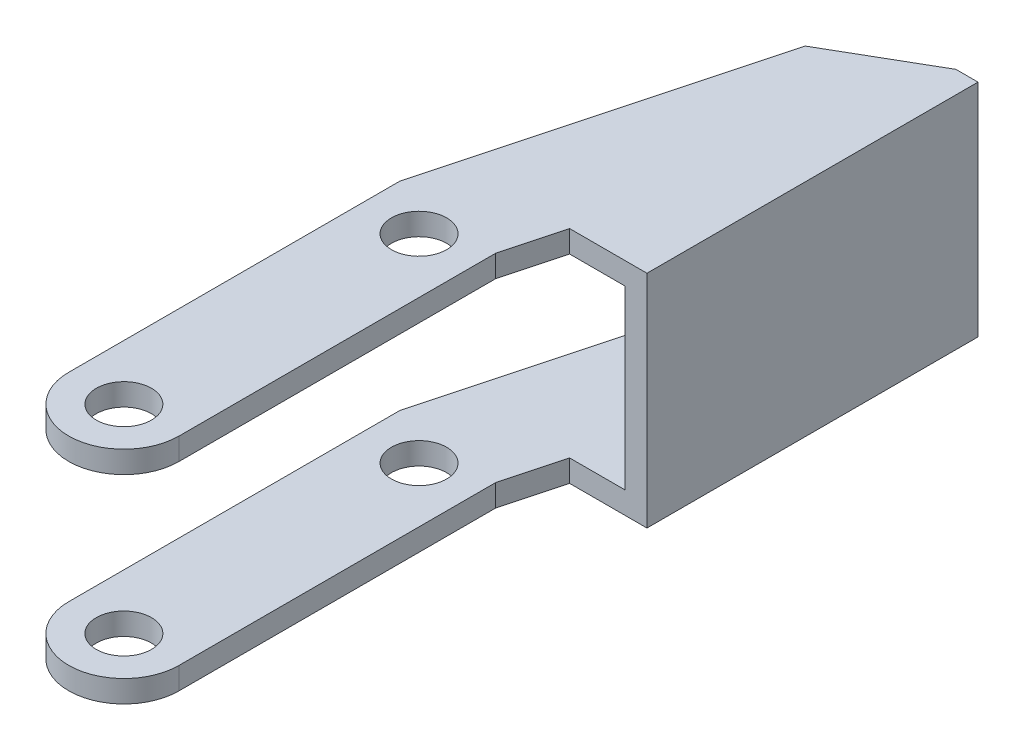
SolidWorks part; units mm, degrees
ref_plane "Front Plane" through (0, 0, 0) normal (0, 0, 1) x (1, 0, 0)
ref_plane "Top Plane" through (0, 0, 0) normal (0, 1, 0) x (1, 0, 0)
ref_plane "Right Plane" through (0, 0, 0) normal (1, 0, 0) x (0, 0, -1)
ref_plane "Plane1" through (-20, 0, 0) normal (-1, 0, 0) x (0, 0, 1)
sketch "Sketch2" plane through (-20, 0, 0) normal (-1, 0, 0) x (0, 0, 1)
  line L1 (-15, 10) -> (15, 10)
  line L2 (-15, 10) -> (-15, -10)
  line L3 (-15, -10) -> (15, -10)
  line L4 (15, 10) -> (15, -10)
  line L5 (-15, 10) -> (15, -10) construction
  line L6 (-15, -10) -> (15, 10) construction
  point P0 (0, 0)
  dimension "D1" = 30
  dimension "D2" = 20
extrude "Boss-Extrude1" add sketch "Sketch2" along normal blind 2
sketch "Sketch3" plane through (0, 10, 0) normal (0, 1, 0) x (1, 0, 0)
  line L0 (-22, 15) -> (-30.6603, 10)
  line L1 (-22, -15) -> (-22, 15) construction
  line L2 (-30.6603, 10) -> (-38.4248, -18.9778)
  line L3 (-22, -15) -> (-27.0062, -15) construction
  line L4 (-28.4248, -20.2943) -> (-27.0062, -15)
  line L5 (-27.0062, -15) -> (-22, -15)
  line L6 (-38.4248, -18.9778) -> (-28.4248, -20.2943) construction
  line L7 (-38.4248, -18.9778) -> (-38.4248, -48.9778)
  line L8 (-28.4248, -20.2943) -> (-28.4248, -48.9778)
  line L10 (-33.4248, -49.03) -> (-33.4248, -22.23) construction
  circle A2 centre (-33.4248, -48.9778) radius 2.5
  arc A3 (-38.4248, -48.9778) -> (-28.4248, -48.9778) centre (-33.4248, -48.9778) ccw
  circle A4 centre (-33.4248, -22.23) radius 2.5
  point P9 (-27.7155, -17.6471)
  dimension "D7" = 26.8
  dimension "D9" = 5
  dimension "D6" = 5
  dimension "D1" = 60
  dimension "D2" = 30
  dimension "D3" = 10
  dimension "D4" = 135
  dimension "D5" = 10
  dimension "D8" = 30
extrude "Boss-Extrude2" add sketch "Sketch3" against normal blind 2
ref_plane "Plane2" through (0, 0, 0) normal (0, -1, 0) x (-1, 0, 0)
mirror "Mirror1" about plane through (0, 0, 0) normal (0, -1, 0) of "Boss-Extrude2"
sketch "Sketch4" plane through (0, -10, 0) normal (0, -1, 0) x (1, 0, 0)
  line L0 (-28.4248, 20.2943) -> (-58.4997, -56.2282)
